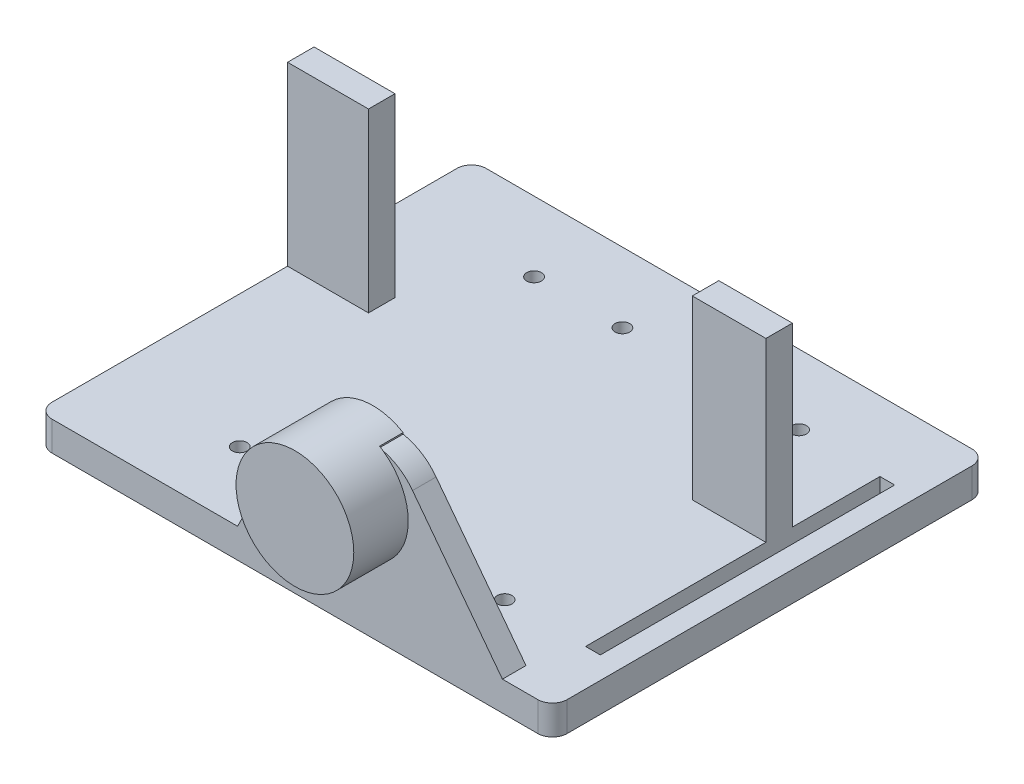
SolidWorks part; units mm, degrees
ref_plane "Alzado" through (0, 0, 0) normal (0, 0, 1) x (1, 0, 0)
ref_plane "Planta" through (0, 0, 0) normal (0, 1, 0) x (1, 0, 0)
ref_plane "Vista lateral" through (0, 0, 0) normal (1, 0, 0) x (0, 0, -1)
sketch "Croquis1" plane through (0, 0, 0) normal (0, 1, 0) x (1, 0, 0)
  line L1 (-17.5, -14.75) -> (17.5, -14.75)
  line L2 (-17.5, -14.75) -> (-17.5, 14.75)
  line L3 (-17.5, 14.75) -> (17.5, 14.75)
  line L4 (17.5, -14.75) -> (17.5, 14.75)
  line L5 (-17.5, -14.75) -> (17.5, 14.75) construction
  line L6 (-17.5, 14.75) -> (17.5, -14.75) construction
  point P0 (0, 0)
  dimension "D1" = 35
  dimension "D2" = 29.5
extrude "Saliente-Extruir1" add sketch "Croquis1" along normal blind 2
sketch "Croquis2" plane through (0, 0, 14.75) normal (0, 0, 1) x (1, 0, 0)
  line L0 (17.5, 2) -> (14.1, 2) construction
  line L1 (-17.5, 2) -> (17.5, 2) construction
  line L2 (14.1, 2) -> (-3.9, 2)
  line L3 (5.1, 2) -> (5.1, 11.5) construction
  line L4 (5.1, 11.5) -> (5.1, 7.9) construction
  line L5 (14.1, 2) -> (7.9921, 10.0438)
  line L6 (-3.9, 2) -> (2.2079, 10.0438)
  arc A0 (2.2079, 10.0438) -> (7.9921, 10.0438) centre (5.1, 7.9) cw
  dimension "D1" = 3.4
  dimension "D2" = 18
extrude "Saliente-Extruir2" add sketch "Croquis2" against normal blind 1.6
sketch "Croquis3" plane through (0, 0, 14.75) normal (0, 0, 1) x (1, 0, 0)
  circle A1 centre (3.7, 8.1) radius 4
extrude "Saliente-Extruir3" add sketch "Croquis3" along normal blind 3.7
sketch "Croquis4" plane through (0, 2, 0) normal (0, 1, 0) x (1, 0, 0)
  line L0 (-17.5, -14.75) -> (-17.5, 2.25) construction
  line L1 (-17.5, 14.75) -> (-17.5, -14.75) construction
  line L2 (-12, 2.25) -> (10, 2.25) construction
  line L3 (-17.5, 2.25) -> (-12, 2.25)
  line L4 (-17.5, 2.25) -> (-17.5, 4.05)
  line L5 (-17.5, 4.05) -> (-12, 4.05)
  line L6 (-12, 2.25) -> (-12, 4.05)
  line L8 (10, 2.25) -> (15, 2.25)
  line L9 (10, 2.25) -> (10, 4.05)
  line L10 (10, 4.05) -> (15, 4.05)
  line L11 (15, 2.25) -> (15, 4.05)
  dimension "D1" = 17
  dimension "D2" = 5.5
  dimension "D3" = 1.8
  dimension "D4" = 22
  dimension "D5" = 5
extrude "Saliente-Extruir4" add sketch "Croquis4" along normal blind 12
sketch "Croquis5" plane through (0, 2, 0) normal (0, 1, 0) x (1, 0, 0)
  line L0 (17.5, 0) -> (15, 0) construction
  line L1 (17.5, -14.75) -> (17.5, 14.75) construction
  line L2 (15, -10) -> (15, 10)
  line L3 (15, 10) -> (16, 10)
  line L4 (16, 10) -> (16, -10)
  line L5 (15, -10) -> (16, -10)
  point P10 (16, 0)
  dimension "D1" = 10
  dimension "D2" = 1
extrude "Cortar-Extruir1" cut sketch "Croquis5" against normal through all
sketch "Croquis6" plane through (0, 0, 0) normal (0, -1, 0) x (1, 0, 0)
  line L0 (-17.5, 0) -> (-8.5, 0) construction
  line L1 (-17.5, -14.75) -> (-17.5, 14.75) construction
  line L2 (-8.5, 0) -> (-8.5, -10) construction
  circle A0 centre (-8.5, -10) radius 0.5005
  circle A1 centre (-2.5, -10) radius 0.5005
  circle A2 centre (3.5, -10) radius 0.5005
  circle A3 centre (9.5, -10) radius 0.5005
  circle A4 centre (-2.5, 10) radius 0.5005
  circle A5 centre (3.5, 10) radius 0.5005
  circle A6 centre (9.5, 10) radius 0.5005
  circle A7 centre (-8.5, 10) radius 0.5005
  dimension "D1" = 9
  dimension "D2" = 10
  dimension "D3" = 4
  dimension "D4" = 2
extrude "Cortar-Extruir2" cut sketch "Croquis6" against normal blind 12
fillet "Redondeo1" radius 1 4 edges at (17.5, 1, -14.75) (17.5, 1, 14.75) (-17.5, 1, 14.75) (-17.5, 1, -14.75)
sketch "Croquis7" plane through (0, 0, 14.75) normal (0, 0, -1) x (-1, 0, 0)
  line L0 (3.9, 2) -> (-0.0522, 9.7413)
  line L1 (-5.7508, 11.5343) -> (-5.7508, 2)
  line L2 (3.9, 2) -> (-14.1, 2) construction
  line L3 (-5.7508, 2) -> (3.9, 2)
  arc A0 (0.134, 6.9596) -> (-5.9705, 11.3932) centre (-3.7, 8.1) ccw construction
  arc A1 (-0.0522, 9.7413) -> (-5.7508, 11.5343) centre (-3.7, 8.1) ccw
extrude "Saliente-Extruir5" add sketch "Croquis7" along normal blind 1.6
